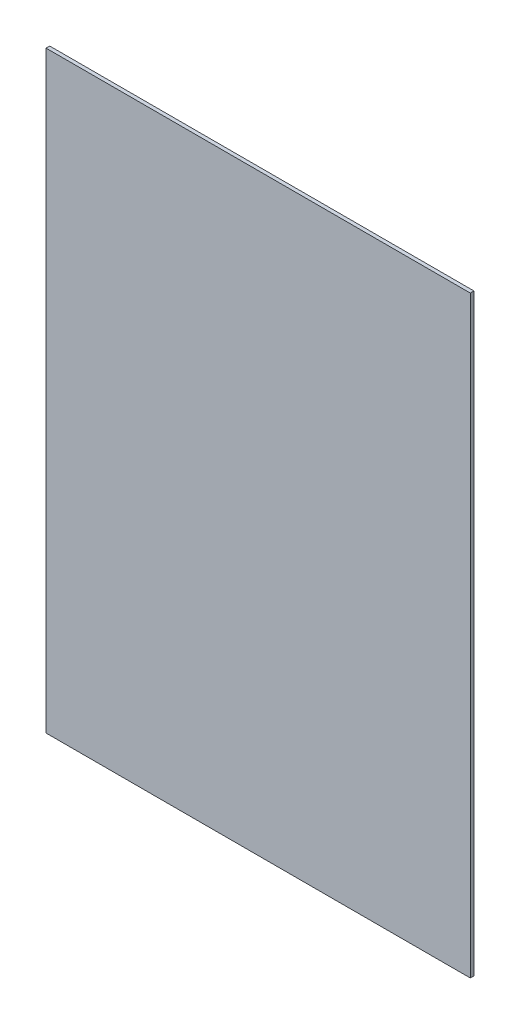
SolidWorks part; units mm, degrees
material "PMMA"
ref_plane "Front Plane" through (0, 0, 0) normal (0, 0, 1) x (1, 0, 0)
ref_plane "Top Plane" through (0, 0, 0) normal (0, 1, 0) x (1, 0, 0)
ref_plane "Right Plane" through (0, 0, 0) normal (1, 0, 0) x (0, 0, -1)
sketch "Sketch1" plane through (0, 0, 0) normal (0, 0, 1) x (1, 0, 0)
  line L1 (-63.65, 178) -> (63.65, 178)
  line L2 (-63.65, 178) -> (-63.65, 0)
  line L3 (-63.65, 0) -> (63.65, 0)
  line L4 (63.65, 178) -> (63.65, 0)
  point P4 (0, 0)
  dimension "D1" = 127.3
  dimension "D2" = 178
extrude "Boss-Extrude1" add sketch "Sketch1" along normal blind 1.1
